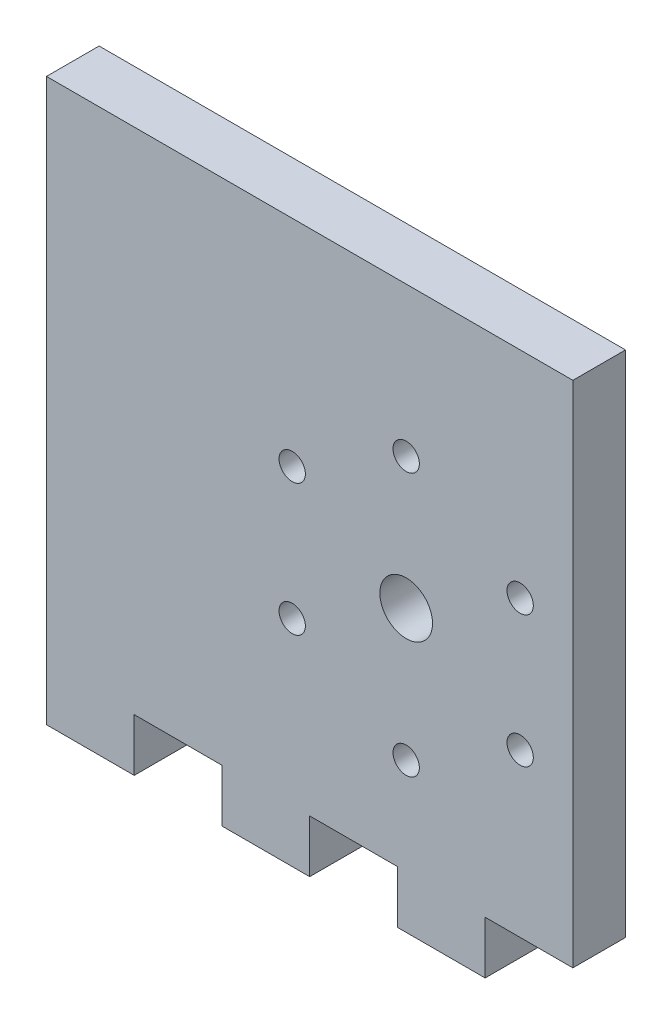
SolidWorks part; units mm, degrees
ref_plane "Alzado" through (0, 0, 0) normal (0, 0, 1) x (1, 0, 0)
ref_plane "Planta" through (0, 0, 0) normal (0, 1, 0) x (1, 0, 0)
ref_plane "Vista lateral" through (0, 0, 0) normal (1, 0, 0) x (0, 0, -1)
sketch "Sketch1" plane through (0, 0, 0) normal (0, 0, 1) x (1, 0, 0)
  line L0 (10, 0) -> (10, 3)
  line L1 (0, 0) -> (10, 0)
  line L2 (0, 0) -> (0, -29)
  line L3 (20.5, 0) -> (20.5, -26) construction
  line L4 (30, 0) -> (30, -26)
  line L5 (0, 0) -> (30, -26) construction
  line L6 (20.5, -13) -> (30, -13) construction
  line L7 (10, 3) -> (15, 3)
  line L8 (15, 3) -> (15, 0)
  line L9 (20, 0) -> (20, 3)
  line L10 (20, 3) -> (25, 3)
  line L11 (25, 3) -> (25, 0)
  line L12 (10, -26) -> (10, -29)
  line L13 (10, -29) -> (15, -29)
  line L14 (15, -29) -> (15, -26)
  line L15 (20, -29) -> (25, -29)
  line L16 (25, -29) -> (25, -26)
  line L17 (20, -29) -> (20, -26)
  line L18 (15, 0) -> (20, 0)
  line L19 (25, 0) -> (30, 0)
  line L20 (25, -26) -> (30, -26)
  line L21 (15, -26) -> (20, -26)
  line L23 (0, -29) -> (5, -29)
  line L24 (5, -29) -> (5, -26)
  line L25 (5, -26) -> (10, -26)
  circle A0 centre (20.5, -13) radius 7.5 construction
  circle A1 centre (20.5, -5.5) radius 0.75
  circle A2 centre (26.9952, -9.25) radius 0.75
  circle A3 centre (26.9952, -16.75) radius 0.75
  circle A4 centre (20.5, -20.5) radius 0.75
  circle A5 centre (14.0048, -16.75) radius 0.75
  circle A6 centre (14.0048, -9.25) radius 0.75
  circle A7 centre (20.5, -13) radius 1.5
  point P0 (0, 0)
  point P43 (20.5, -13)
  dimension "D7" = 15
  dimension "D8" = 1.5
  dimension "D10" = 3
  dimension "D1" = 30
  dimension "D2" = 5
  dimension "D3" = 3
  dimension "D4" = 29
  dimension "D5" = 3
  dimension "D6" = 9.5
  dimension "D9" = 6
extrude "Boss-Extrude1" add sketch "Sketch1" along normal blind 3
sketch "Croquis1" plane through (0, 0, 3) normal (0, 0, 1) x (1, 0, 0)
  line L1 (10, 0) -> (25, 0)
  line L2 (10, 0) -> (10, 6.7189)
  line L3 (10, 6.7189) -> (25, 6.7189)
  line L4 (25, 0) -> (25, 6.7189)
  point P5 (25, 3.3595)
  dimension "D1" = 6.7189
  dimension "D2" = 15
extrude "Cortar-Extruir1" cut sketch "Croquis1" against normal up to next
sketch "Croquis2" plane through (0, 0, 3) normal (0, 0, 1) x (1, 0, 0)
  line L1 (30, 0) -> (0, 0)
  line L2 (30, 0) -> (30, 3)
  line L3 (30, 3) -> (0, 3)
  line L4 (0, 0) -> (0, 3)
  dimension "D1" = 30
  dimension "D2" = 3
extrude "Saliente-Extruir1" add sketch "Croquis2" against normal blind 3
